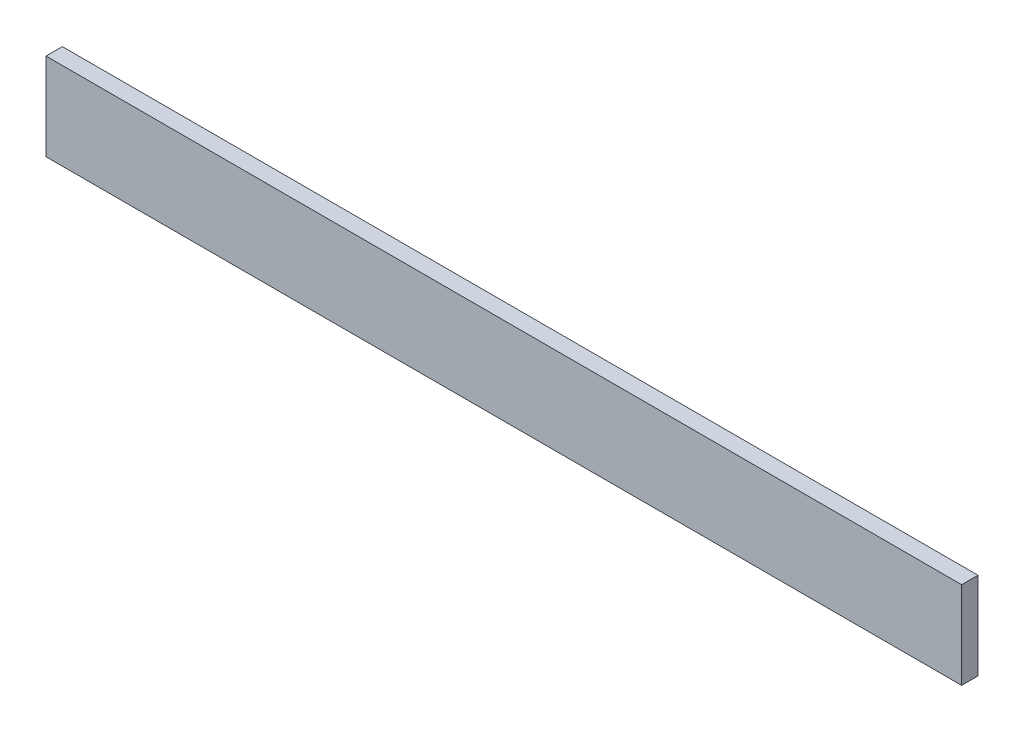
SolidWorks part; units mm, degrees
material "Pine"
ref_plane "Front Plane" through (0, 0, 0) normal (0, 0, 1) x (1, 0, 0)
ref_plane "Top Plane" through (0, 0, 0) normal (0, 1, 0) x (1, 0, 0)
ref_plane "Right Plane" through (0, 0, 0) normal (1, 0, 0) x (0, 0, -1)
sketch "Sketch1" plane through (0, 0, 0) normal (0, 0, 1) x (1, 0, 0)
  line L1 (-533.4, -50.8) -> (533.4, -50.8)
  line L2 (-533.4, -50.8) -> (-533.4, 50.8)
  line L3 (-533.4, 50.8) -> (533.4, 50.8)
  line L4 (533.4, -50.8) -> (533.4, 50.8)
  line L5 (-533.4, -50.8) -> (533.4, 50.8) construction
  line L6 (-533.4, 50.8) -> (533.4, -50.8) construction
  point P0 (0, 0)
  dimension "D1" = 1066.8
  dimension "D2" = 101.6
extrude "Boss-Extrude1" add sketch "Sketch1" along normal blind 19.05
